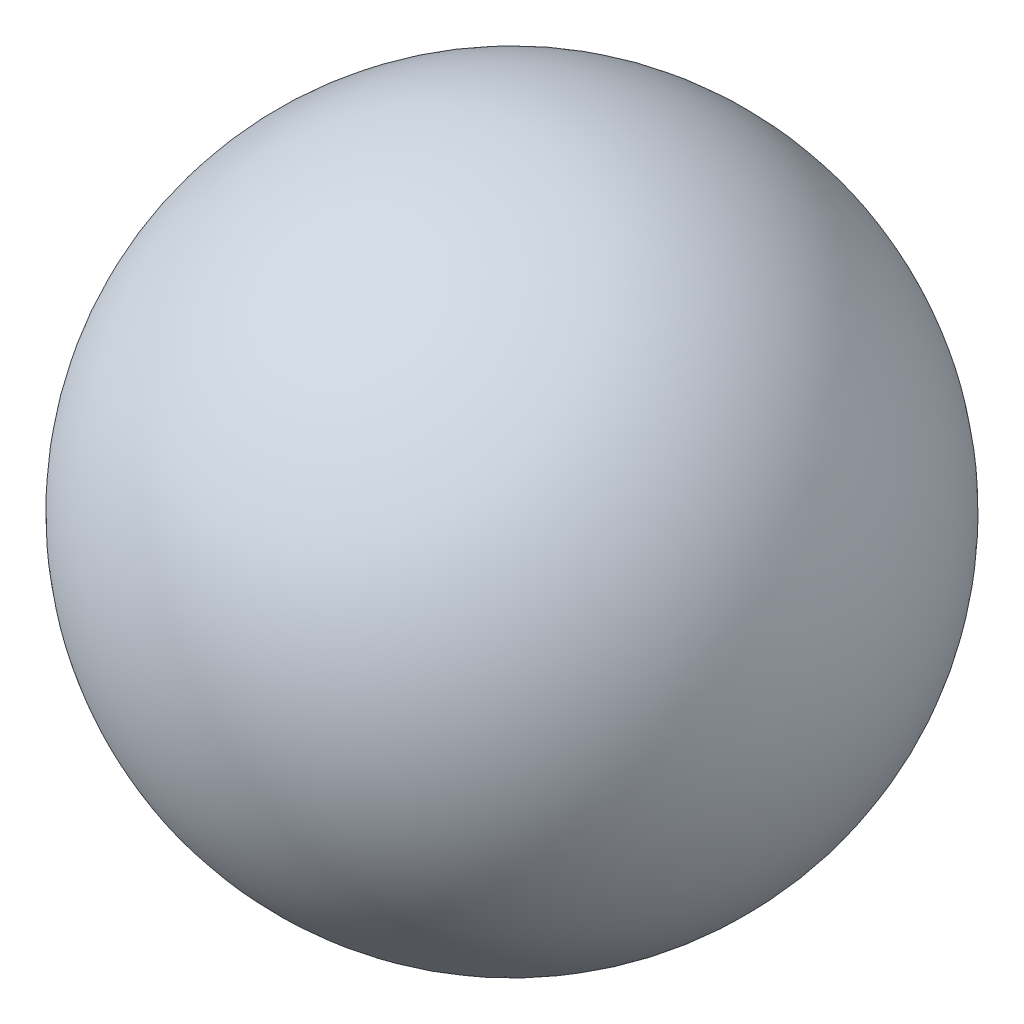
SolidWorks part; units mm, degrees
ref_plane "Front Plane" through (0, 0, 0) normal (0, 0, 1) x (1, 0, 0)
ref_plane "Top Plane" through (0, 0, 0) normal (0, 1, 0) x (1, 0, 0)
ref_plane "Right Plane" through (0, 0, 0) normal (1, 0, 0) x (0, 0, -1)
sketch "Sketch1" plane through (0, 0, 0) normal (0, 1, 0) x (1, 0, 0)
  line L0 (0, 15) -> (0, -15)
  arc A0 (0, 15) -> (0, -15) centre (0, 0) ccw
  dimension "D1" = 30
revolve "Revolve1" add sketch "Sketch1" angle 360 about L0
